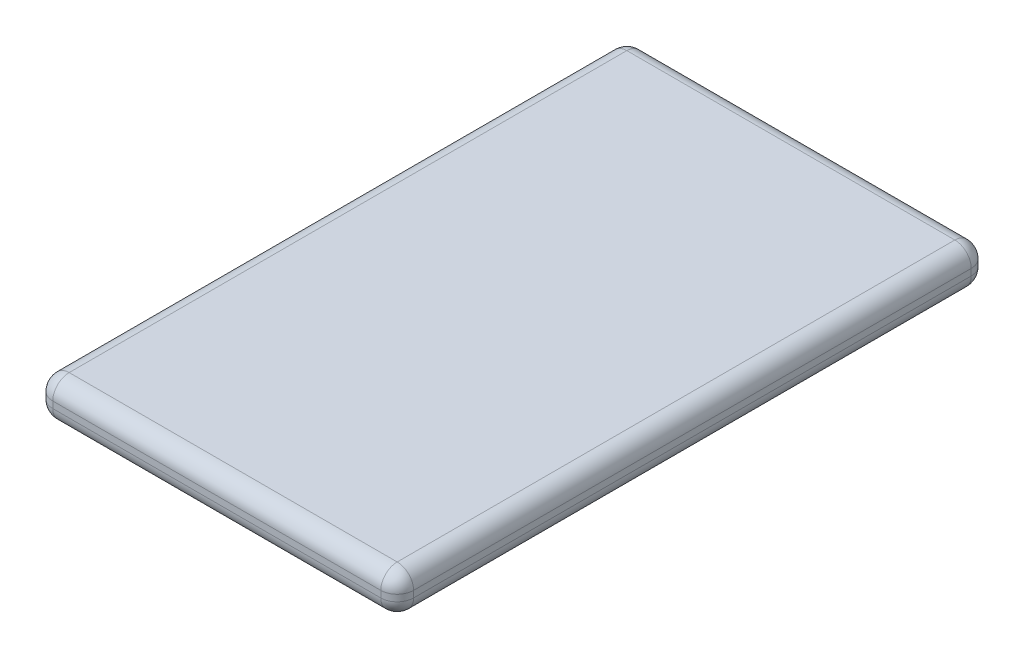
SolidWorks part; units mm, degrees
ref_plane "Front Plane" through (0, 0, 0) normal (0, 0, 1) x (1, 0, 0)
ref_plane "Top Plane" through (0, 0, 0) normal (0, 1, 0) x (1, 0, 0)
ref_plane "Right Plane" through (0, 0, 0) normal (1, 0, 0) x (0, 0, -1)
sketch "Sketch1" plane through (0, 0, 0) normal (0, 1, 0) x (1, 0, 0)
  line L1 (0, 0) -> (55, 0)
  line L2 (0, 0) -> (0, -90)
  line L3 (0, -90) -> (55, -90)
  line L4 (55, 0) -> (55, -90)
extrude "Boss-Extrude1" add sketch "Sketch1" along normal blind 6
fillet "Fillet1" radius 2.5 12 edges at (0, 3, 0) (0, 3, 90) (55, 3, 90) (55, 3, 0) (27.5, 0, 90) (55, 0, 45) (27.5, 0, 0) (0, 0, 45) (27.5, 6, 0) (55, 6, 45) (27.5, 6, 90) (0, 6, 45)
